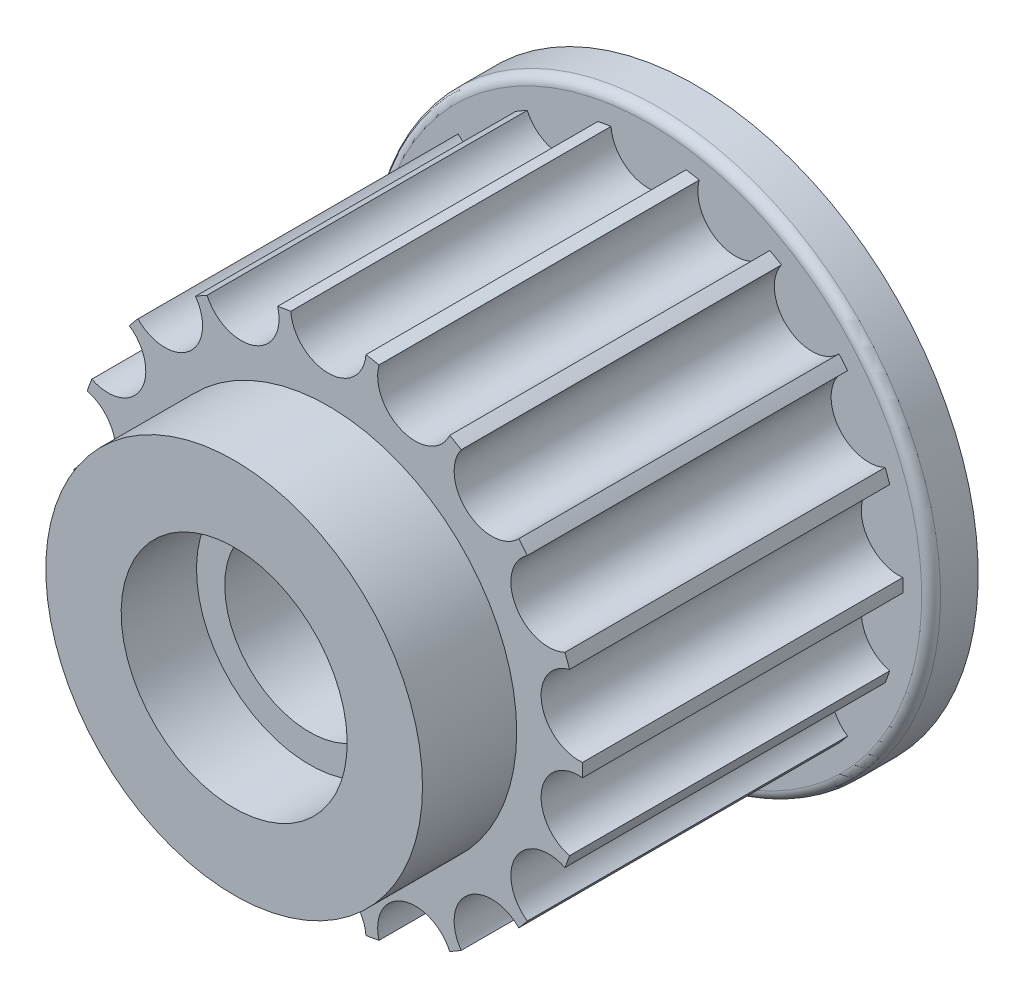
SolidWorks part; units mm, degrees
ref_plane "Front Plane" through (0, 0, 0) normal (0, 0, 1) x (1, 0, 0)
ref_plane "Top Plane" through (0, 0, 0) normal (0, 1, 0) x (1, 0, 0)
ref_plane "Right Plane" through (0, 0, 0) normal (1, 0, 0) x (0, 0, -1)
sketch "Croquis1" plane through (0, 0, 0) normal (0, 0, 1) x (1, 0, 0)
  circle A0 centre (0, 0) radius 13.5
extrude "Saliente-Extruir1" add sketch "Croquis1" along normal blind 17
sketch "Croquis2" plane through (0, 0, 17) normal (0, 0, 1) x (1, 0, 0)
  circle A1 centre (0, 0) radius 13.5 construction
  arc A2 (-1.9945, 13.3519) -> (1.9945, 13.3519) centre (0, 13.5) ccw
  arc A4 (2.6924, 13.2288) -> (6.4408, 11.8645) centre (4.6173, 12.6859) ccw
  arc A5 (7.0545, 11.5102) -> (10.1103, 8.9461) centre (8.6776, 10.3416) ccw
  arc A6 (10.5658, 8.4032) -> (12.5603, 4.9486) centre (11.6913, 6.75) ccw
  arc A7 (12.8027, 4.2827) -> (13.4953, 0.3543) centre (13.2949, 2.3443) ccw
  arc A8 (13.4953, -0.3543) -> (12.8027, -4.2827) centre (13.2949, -2.3443) ccw
  arc A9 (12.5603, -4.9486) -> (10.5658, -8.4032) centre (11.6913, -6.75) ccw
  arc A10 (10.1103, -8.9461) -> (7.0545, -11.5102) centre (8.6776, -10.3416) ccw
  arc A11 (6.4408, -11.8645) -> (2.6924, -13.2288) centre (4.6173, -12.6859) ccw
  arc A12 (1.9945, -13.3519) -> (-1.9945, -13.3519) centre (0, -13.5) ccw
  arc A13 (-2.6924, -13.2288) -> (-6.4408, -11.8645) centre (-4.6173, -12.6859) ccw
  arc A14 (-7.0545, -11.5102) -> (-10.1103, -8.9461) centre (-8.6776, -10.3416) ccw
  arc A15 (-10.5658, -8.4032) -> (-12.5603, -4.9486) centre (-11.6913, -6.75) ccw
  arc A16 (-12.8027, -4.2827) -> (-13.4953, -0.3543) centre (-13.2949, -2.3443) ccw
  arc A17 (-13.4953, 0.3543) -> (-12.8027, 4.2827) centre (-13.2949, 2.3443) ccw
  arc A18 (-12.5603, 4.9486) -> (-10.5658, 8.4032) centre (-11.6913, 6.75) ccw
  arc A19 (-10.1103, 8.9461) -> (-7.0545, 11.5102) centre (-8.6776, 10.3416) ccw
  arc A20 (-6.4408, 11.8645) -> (-2.6924, 13.2288) centre (-4.6173, 12.6859) ccw
  arc A21 (-7.0545, 11.5102) -> (-6.4408, 11.8645) centre (-4.9889, 8.641) cw
  arc A22 (-2.6924, 13.2288) -> (-1.9945, 13.3519) centre (-1.7326, 9.8262) cw
  arc A23 (1.9945, 13.3519) -> (2.6924, 13.2288) centre (1.7326, 9.8262) cw
  arc A24 (6.4408, 11.8645) -> (7.0545, 11.5102) centre (4.9889, 8.641) cw
  arc A25 (10.1103, 8.9461) -> (10.5658, 8.4032) centre (7.6434, 6.4136) cw
  arc A26 (12.5603, 4.9486) -> (12.8027, 4.2827) centre (9.3761, 3.4126) cw
  arc A27 (13.4953, 0.3543) -> (13.4953, -0.3543) centre (9.9778, 0) cw
  arc A28 (12.8027, -4.2827) -> (12.5603, -4.9486) centre (9.3761, -3.4126) cw
  arc A29 (10.5658, -8.4032) -> (10.1103, -8.9461) centre (7.6434, -6.4136) cw
  arc A30 (7.0545, -11.5102) -> (6.4408, -11.8645) centre (4.9889, -8.641) cw
  arc A31 (2.6924, -13.2288) -> (1.9945, -13.3519) centre (1.7326, -9.8262) cw
  arc A32 (-1.9945, -13.3519) -> (-2.6924, -13.2288) centre (-1.7326, -9.8262) cw
  arc A33 (-6.4408, -11.8645) -> (-7.0545, -11.5102) centre (-4.9889, -8.641) cw
  arc A34 (-10.1103, -8.9461) -> (-10.5658, -8.4032) centre (-7.6434, -6.4136) cw
  arc A35 (-12.5603, -4.9486) -> (-12.8027, -4.2827) centre (-9.3761, -3.4126) cw
  arc A36 (-13.4953, -0.3543) -> (-13.4953, 0.3543) centre (-9.9778, 0) cw
  arc A37 (-12.8027, 4.2827) -> (-12.5603, 4.9486) centre (-9.3761, 3.4126) cw
  arc A38 (-10.5658, 8.4032) -> (-10.1103, 8.9461) centre (-7.6434, 6.4136) cw
  arc A40 (-1.9945, 13.3519) -> (1.9945, 13.3519) centre (0, 13.5) ccw
  arc A41 (-1.9945, 13.3519) -> (1.9945, 13.3519) centre (0, 0) cw
  arc A42 (2.6924, 13.2288) -> (6.4408, 11.8645) centre (0, 0) cw
  arc A43 (2.6924, 13.2288) -> (6.4408, 11.8645) centre (4.6173, 12.6859) ccw
  arc A44 (7.0545, 11.5102) -> (10.1103, 8.9461) centre (0, 0) cw
  arc A45 (7.0545, 11.5102) -> (10.1103, 8.9461) centre (8.6776, 10.3416) ccw
  arc A46 (10.5658, 8.4032) -> (12.5603, 4.9486) centre (0, 0) cw
  arc A47 (10.5658, 8.4032) -> (12.5603, 4.9486) centre (11.6913, 6.75) ccw
  arc A48 (12.8027, 4.2827) -> (13.4953, 0.3543) centre (0, 0) cw
  arc A49 (12.8027, 4.2827) -> (13.4953, 0.3543) centre (13.2949, 2.3443) ccw
  arc A50 (13.4953, -0.3543) -> (12.8027, -4.2827) centre (0, 0) cw
  arc A51 (13.4953, -0.3543) -> (12.8027, -4.2827) centre (13.2949, -2.3443) ccw
  arc A52 (12.5603, -4.9486) -> (10.5658, -8.4032) centre (0, 0) cw
  arc A53 (12.5603, -4.9486) -> (10.5658, -8.4032) centre (11.6913, -6.75) ccw
  arc A54 (10.1103, -8.9461) -> (7.0545, -11.5102) centre (0, 0) cw
  arc A55 (10.1103, -8.9461) -> (7.0545, -11.5102) centre (8.6776, -10.3416) ccw
  arc A56 (6.4408, -11.8645) -> (2.6924, -13.2288) centre (0, 0) cw
  arc A57 (6.4408, -11.8645) -> (2.6924, -13.2288) centre (4.6173, -12.6859) ccw
  arc A58 (1.9945, -13.3519) -> (-1.9945, -13.3519) centre (0, 0) cw
  arc A59 (1.9945, -13.3519) -> (-1.9945, -13.3519) centre (0, -13.5) ccw
  arc A60 (-2.6924, -13.2288) -> (-6.4408, -11.8645) centre (0, 0) cw
  arc A61 (-2.6924, -13.2288) -> (-6.4408, -11.8645) centre (-4.6173, -12.6859) ccw
  arc A62 (-7.0545, -11.5102) -> (-10.1103, -8.9461) centre (0, 0) cw
  arc A63 (-7.0545, -11.5102) -> (-10.1103, -8.9461) centre (-8.6776, -10.3416) ccw
  arc A64 (-10.5658, -8.4032) -> (-12.5603, -4.9486) centre (0, 0) cw
  arc A65 (-10.5658, -8.4032) -> (-12.5603, -4.9486) centre (-11.6913, -6.75) ccw
  arc A66 (-12.8027, -4.2827) -> (-13.4953, -0.3543) centre (0, 0) cw
  arc A67 (-12.8027, -4.2827) -> (-13.4953, -0.3543) centre (-13.2949, -2.3443) ccw
  arc A68 (-13.4953, 0.3543) -> (-12.8027, 4.2827) centre (0, 0) cw
  arc A69 (-13.4953, 0.3543) -> (-12.8027, 4.2827) centre (-13.2949, 2.3443) ccw
  arc A70 (-12.5603, 4.9486) -> (-10.5658, 8.4032) centre (0, 0) cw
  arc A71 (-12.5603, 4.9486) -> (-10.5658, 8.4032) centre (-11.6913, 6.75) ccw
  arc A72 (-10.1103, 8.9461) -> (-7.0545, 11.5102) centre (0, 0) cw
  arc A73 (-10.1103, 8.9461) -> (-7.0545, 11.5102) centre (-8.6776, 10.3416) ccw
  arc A74 (-6.4408, 11.8645) -> (-2.6924, 13.2288) centre (0, 0) cw
  arc A75 (-6.4408, 11.8645) -> (-2.6924, 13.2288) centre (-4.6173, 12.6859) ccw
  point P64 (0, 0)
  point P116 (0, 0)
  point P132 (0, 0)
  circle M39 centre (0, 0) radius 13.5
  dimension "D1" = 18
  dimension "D2" = 18
  dimension "D3" = 18
extrude "Cortar-Extruir5" cut sketch "Croquis2" against normal blind 26 contours A20 M39 | A19 M39 | A18 M39 | A2 M39 | A4 M39 | A5 M39 | A6 M39 | A7 M39 | A8 M39 | A9 M39 | A10 M39 | A11 M39 | A12 M39 | A13 M39 | A14 M39 | A15 M39 | A16 M39 | A17 M39
sketch "Croquis8" plane through (0, 0, 17) normal (0, 0, 1) x (1, 0, 0)
  circle A0 centre (0, 0) radius 10
extrude "Saliente-Extruir2" add sketch "Croquis8" along normal blind 5
sketch "Croquis9" plane through (0, 0, 22) normal (0, 0, 1) x (1, 0, 0)
  circle A0 centre (0, 0) radius 4.5
extrude "Cortar-Extruir6" cut sketch "Croquis9" against normal blind 45
sketch "Croquis10" plane through (0, 0, 22) normal (0, 0, 1) x (1, 0, 0)
  circle A0 centre (0, 0) radius 6
extrude "Cortar-Extruir8" cut sketch "Croquis10" against normal blind 4
sketch "Croquis12" plane through (0, 0, 0) normal (0, 0, -1) x (-1, 0, 0)
  circle A0 centre (0, 0) radius 15
extrude "Saliente-Extruir4" add sketch "Croquis12" along normal blind 2.5
sketch "Croquis13" plane through (0, 0, -2.5) normal (0, 0, -1) x (-1, 0, 0)
  circle A0 centre (0, 0) radius 4.5
extrude "Cortar-Extruir9" cut sketch "Croquis13" against normal blind 25
sketch "Croquis14" plane through (0, 0, -2.5) normal (0, 0, -1) x (-1, 0, 0)
  circle A0 centre (0, 0) radius 10
extrude "Saliente-Extruir5" add sketch "Croquis14" along normal blind 0.5
sketch "Croquis15" plane through (0, 0, -3) normal (0, 0, -1) x (-1, 0, 0)
  circle A0 centre (0, 0) radius 6
extrude "Cortar-Extruir10" cut sketch "Croquis15" against normal blind 2
sketch "Croquis16" plane through (0, 0, 22) normal (0, 0, 1) x (1, 0, 0)
  line L0 (0, 0) -> (0, 4.5) construction
  line L3 (-1.5, 4.2426) -> (-1.5, 5.8126)
  line L4 (-1.5, 5.8126) -> (1.5, 5.8126)
  line L5 (1.5, 4.2426) -> (1.5, 5.8126)
  arc A0 (1.5, 4.2426) -> (-1.5, 4.2426) centre (0, 0) ccw
  dimension "D1" = 3
  dimension "D2" = 1.57
  dimension "D3" = 1.57
extrude "Cortar-Extruir12" cut sketch "Croquis16" against normal blind 50
fillet "Redondeo1" radius 0.5 1 edges at (-15, 0, 0)
